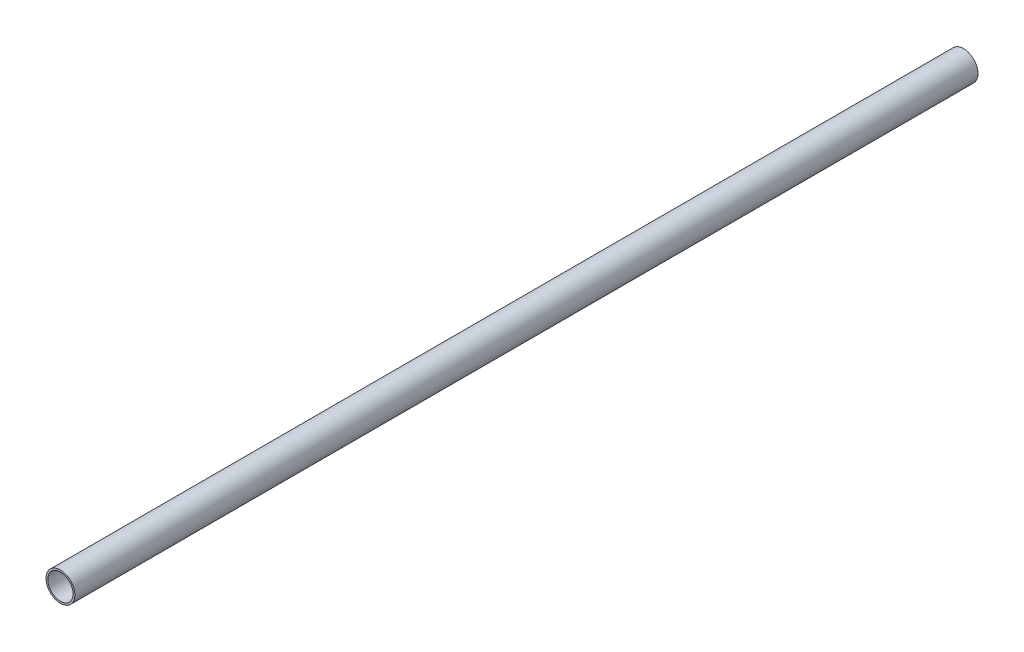
SolidWorks part; units mm, degrees
material "Thornel Mat VMA"
ref_plane "Front Plane" through (0, 0, 0) normal (0, 0, 1) x (1, 0, 0)
ref_plane "Top Plane" through (0, 0, 0) normal (0, 1, 0) x (1, 0, 0)
ref_plane "Right Plane" through (0, 0, 0) normal (1, 0, 0) x (0, 0, -1)
sketch "Sketch1" plane through (0, 0, 0) normal (0, 0, 1) x (1, 0, 0)
  circle A0 centre (0, 0) radius 8
  circle A1 centre (0, 0) radius 7
  dimension "D1" = 16
  dimension "D2" = 14
extrude "Boss-Extrude1" add sketch "Sketch1" along normal blind 500
